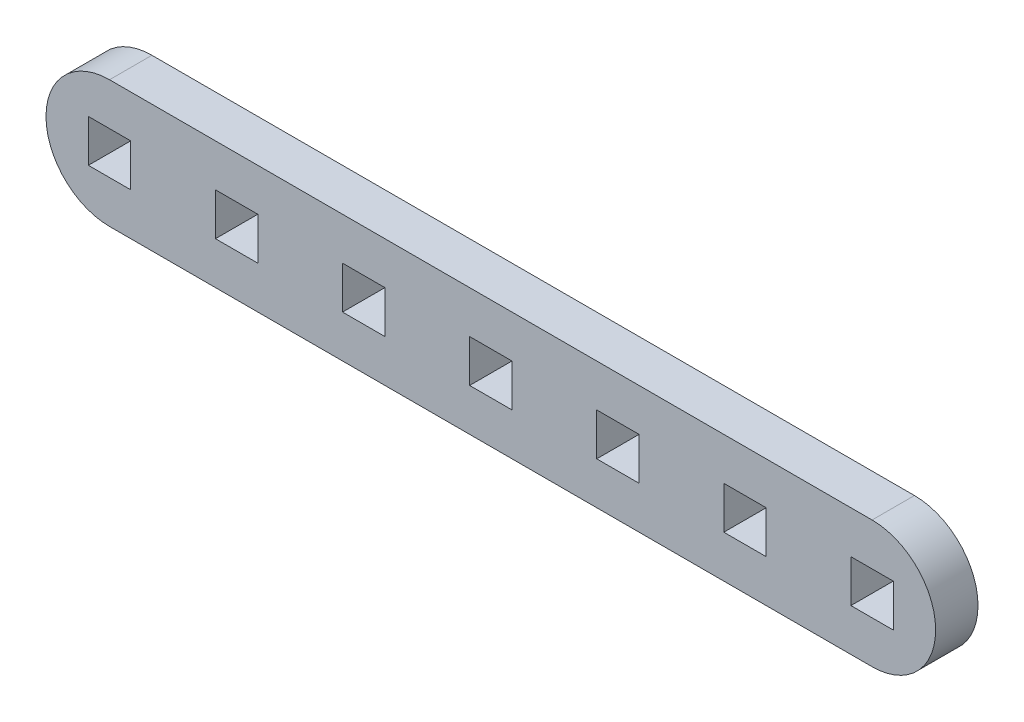
SolidWorks part; units mm, degrees
ref_plane "Alzado" through (0, 0, 0) normal (0, 0, 1) x (1, 0, 0)
ref_plane "Planta" through (0, 0, 0) normal (0, 1, 0) x (1, 0, 0)
ref_plane "Vista lateral" through (0, 0, 0) normal (1, 0, 0) x (0, 0, -1)
sketch "Model" plane through (0, 0, 0) normal (0, 0, 1) x (1, 0, 0)
  line L0 (10.3708, 294.4912) -> (10.3708, 291.4912)
  line L1 (13.3708, 294.4912) -> (10.3708, 294.4912)
  line L2 (13.3708, 291.4912) -> (13.3708, 294.4912)
  line L3 (10.3708, 291.4912) -> (13.3708, 291.4912)
  line L4 (19.3708, 294.4912) -> (19.3708, 291.4912)
  line L5 (22.3708, 294.4912) -> (19.3708, 294.4912)
  line L6 (22.3708, 291.4912) -> (22.3708, 294.4912)
  line L7 (19.3708, 291.4912) -> (22.3708, 291.4912)
  line L8 (28.3708, 294.4912) -> (28.3708, 291.4912)
  line L9 (31.3708, 294.4912) -> (28.3708, 294.4912)
  line L10 (31.3708, 291.4912) -> (31.3708, 294.4912)
  line L11 (28.3708, 291.4912) -> (31.3708, 291.4912)
  line L12 (37.3708, 294.4912) -> (37.3708, 291.4912)
  line L13 (40.3708, 294.4912) -> (37.3708, 294.4912)
  line L14 (40.3708, 291.4912) -> (40.3708, 294.4912)
  line L15 (37.3708, 291.4912) -> (40.3708, 291.4912)
  line L16 (46.3708, 294.4912) -> (46.3708, 291.4912)
  line L17 (49.3708, 294.4912) -> (46.3708, 294.4912)
  line L18 (49.3708, 291.4912) -> (49.3708, 294.4912)
  line L19 (46.3708, 291.4912) -> (49.3708, 291.4912)
  line L20 (55.3708, 294.4912) -> (55.3708, 291.4912)
  line L21 (58.3708, 294.4912) -> (55.3708, 294.4912)
  line L22 (58.3708, 291.4912) -> (58.3708, 294.4912)
  line L23 (55.3708, 291.4912) -> (58.3708, 291.4912)
  line L24 (64.3708, 294.4912) -> (64.3708, 291.4912)
  line L25 (67.3708, 294.4912) -> (64.3708, 294.4912)
  line L26 (67.3708, 291.4912) -> (67.3708, 294.4912)
  line L27 (64.3708, 291.4912) -> (67.3708, 291.4912)
  line L28 (11.8708, 297.4912) -> (65.8708, 297.4912)
  line L29 (11.8708, 288.4912) -> (65.8708, 288.4912)
  arc A0 (65.8708, 288.4912) -> (65.8708, 297.4912) centre (65.8708, 292.9912) ccw
  arc A1 (11.8708, 297.4912) -> (11.8708, 288.4912) centre (11.8708, 292.9912) ccw
extrude "Saliente-Extruir1" add sketch "Model" along normal blind 3
